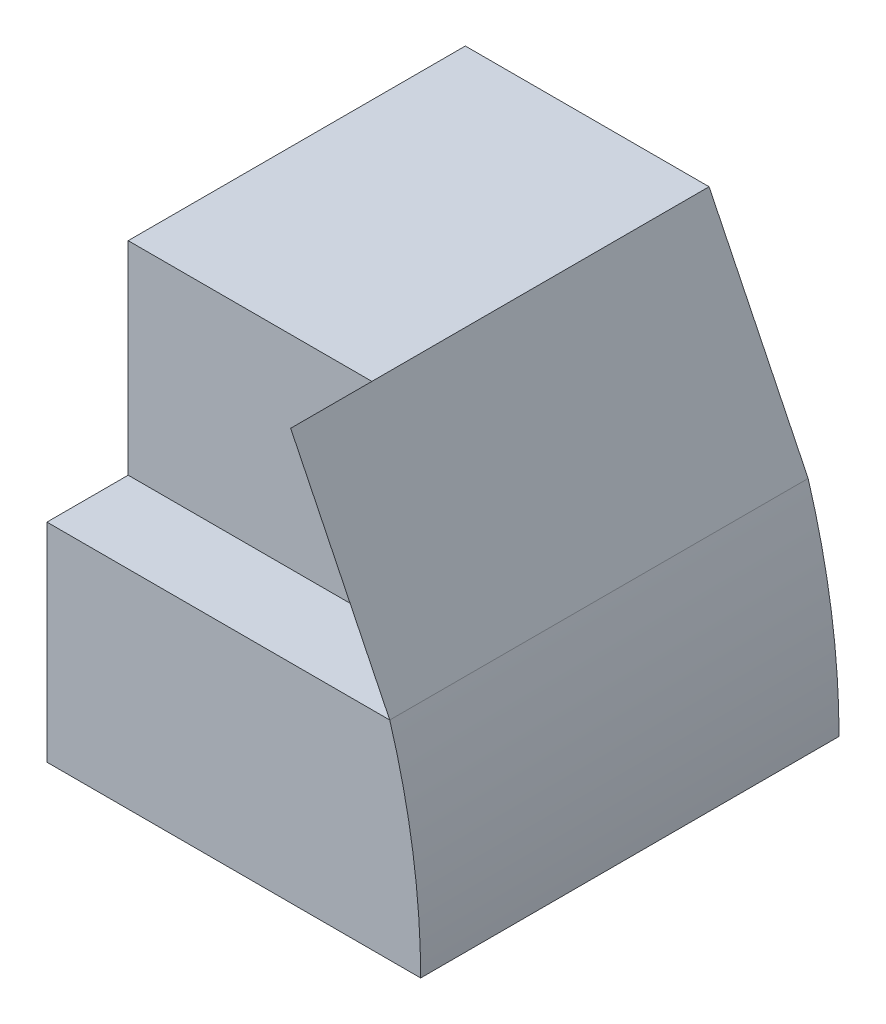
SolidWorks part; units mm, degrees
material "AISI 1020"
ref_plane "Спереди" through (0, 0, 0) normal (0, 0, 1) x (1, 0, 0)
ref_plane "Сверху" through (0, 0, 0) normal (0, 1, 0) x (1, 0, 0)
ref_plane "Справа" through (0, 0, 0) normal (1, 0, 0) x (0, 0, -1)
sketch "Эскиз1" plane through (0, 0, 0) normal (0, 0, 1) x (1, 0, 0)
  line L0 (8801.125, 0) -> (4201.125, 0)
  line L1 (4201.125, 0) -> (4201.125, 5060)
  line L2 (4201.125, 5060) -> (7201.125, 5060)
  line L3 (4201.125, 2560) -> (8420.582, 2560)
  line L4 (7201.125, 5060) -> (7201.125, 2560)
  arc A0 (8801.125, 0) -> (0, 8801.125) centre (0, 0) ccw
  dimension "D1" = 3000
  dimension "D2" = 4600
  dimension "D3" = 2500
  dimension "D4" = 2560
sketch "Эскиз2" plane through (0, 0, 0) normal (0, 0, 1) x (1, 0, 0)
  line L0 (4201.125, 5060) -> (7201.125, 5060) construction
  line L1 (4201.125, 0) -> (4201.125, 5060) construction
  line L2 (8801.125, 0) -> (4201.125, 0) construction
  line L3 (4201.125, 5060) -> (7201.125, 5060)
  line L4 (8801.125, 0) -> (4201.125, 0)
  line L5 (4201.125, 0) -> (4201.125, 5060)
  line L6 (7201.125, 5060) -> (7201.125, 2560) construction
  line L7 (7201.125, 5060) -> (7201.125, 2560)
  line L8 (7201.125, 2560) -> (8420.582, 2560)
  arc A0 (8420.582, 2560) -> (8801.125, 0) centre (0, 0) cw
  arc A1 (8801.125, 0) -> (0, 8801.125) centre (0, 0) ccw construction
extrude "Бобышка-Вытянуть1" add sketch "Эскиз2" along normal blind 5150
surface "Поверхность-Плоскость1"
sketch "Эскиз3" plane through (4201.125, 0, 0) normal (-1, 0, 0) x (0, 0, 1)
  line L0 (5150, 2560) -> (0, 2560) construction
  line L1 (5150, 5060) -> (4150, 5060)
  line L2 (5150, 5060) -> (5150, 2560)
  line L3 (5150, 2560) -> (4150, 2560)
  line L4 (4150, 5060) -> (4150, 2560)
  dimension "D1" = 1000
extrude "Вырез-Вытянуть1" cut sketch "Эскиз3" against normal through all
